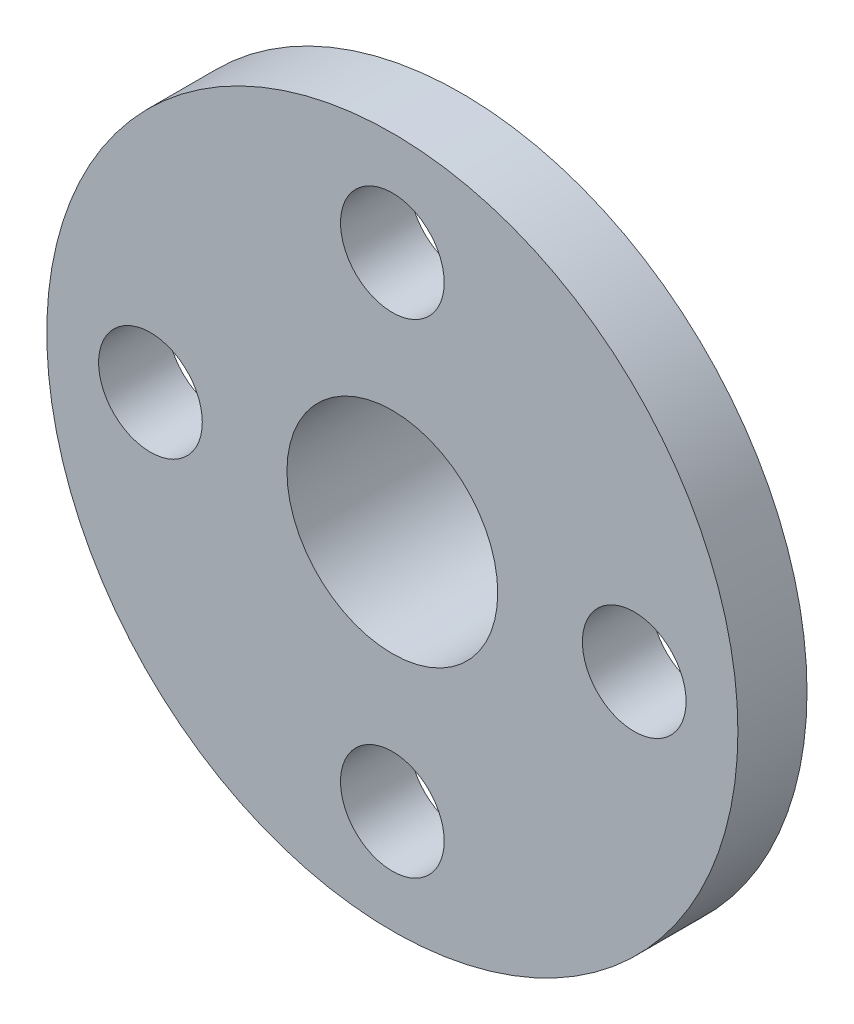
SolidWorks part; units mm, degrees
ref_plane "Front Plane" through (0, 0, 0) normal (0, 0, 1) x (1, 0, 0)
ref_plane "Top Plane" through (0, 0, 0) normal (0, 1, 0) x (1, 0, 0)
ref_plane "Right Plane" through (0, 0, 0) normal (1, 0, 0) x (0, 0, -1)
sketch "Metal_disc_OD20_thickness2_profile" plane through (0, 0, 0) normal (0, 0, 1) x (1, 0, 0)
  circle A0 centre (0, 0) radius 10
  circle A1 centre (0, 0) radius 3.05
  dimension "D1" = 20
  dimension "D2" = 6.1
extrude "Metal_disc_OD20_thickness2" add sketch "Metal_disc_OD20_thickness2_profile" along normal blind 2
sketch "Purchased_25T_hub_envelope_OD9_profile" plane through (0, 0, 0) normal (0, 0, 1) x (1, 0, 0)
  circle A0 centre (0, 0) radius 4.5
  circle A1 centre (0, 0) radius 3.05
  dimension "D1" = 9
  dimension "D2" = 6.1
extrude "Purchased_25T_hub_envelope_OD9" add sketch "Purchased_25T_hub_envelope_OD9_profile" along normal blind 2.5 from offset 2.5
sketch "Four_M3_tapped_hole_envelopes_PCD14_profile" plane through (0, 0, 0) normal (0, 0, 1) x (1, 0, 0)
  circle A0 centre (-7, 0) radius 1.5
  circle A1 centre (7, 0) radius 1.5
  circle A2 centre (0, -7) radius 1.5
  circle A3 centre (0, 7) radius 1.5
  dimension "D1" = 3
  dimension "D2" = 3
  dimension "D3" = 3
  dimension "D4" = 3
extrude "Four_M3_tapped_hole_envelopes_PCD14" cut sketch "Four_M3_tapped_hole_envelopes_PCD14_profile" along normal through all from offset 50
